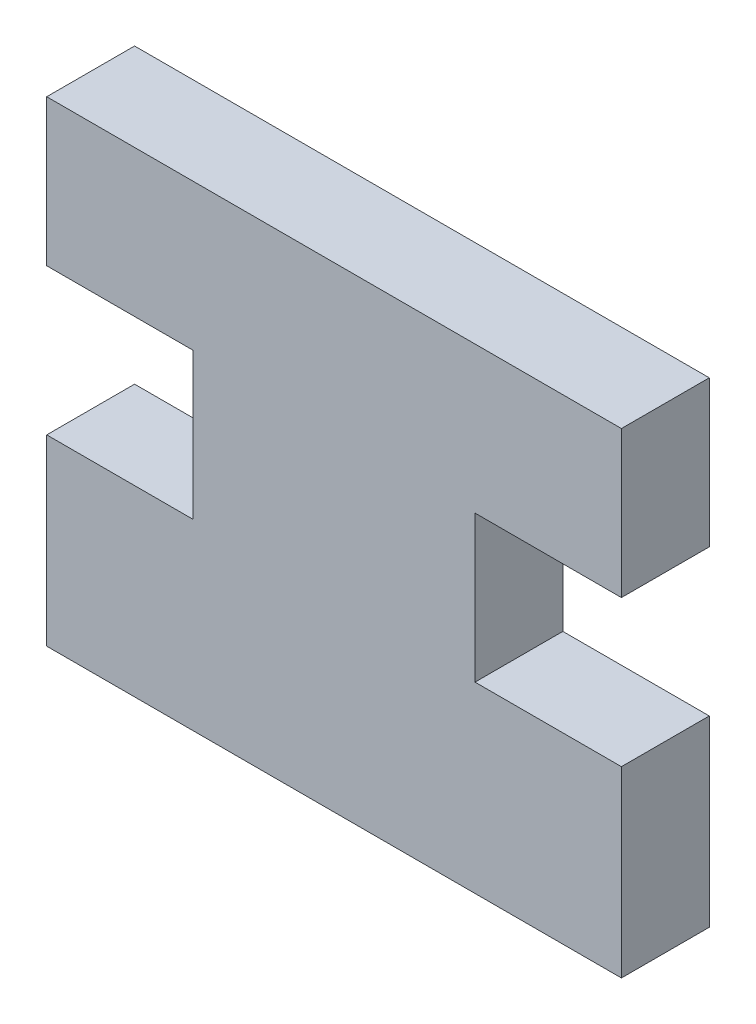
SolidWorks part; units mm, degrees
material "PBT General Purpose"
ref_plane "Front Plane" through (0, 0, 0) normal (0, 0, 1) x (1, 0, 0)
ref_plane "Top Plane" through (0, 0, 0) normal (0, 1, 0) x (1, 0, 0)
ref_plane "Right Plane" through (0, 0, 0) normal (1, 0, 0) x (0, 0, -1)
sketch "Sketch1" plane through (0, 0, 0) normal (0, 0, 1) x (1, 0, 0)
  line L0 (0, 0) -> (0, 0.5)
  line L1 (0, 0.5) -> (0.4, 0.5)
  line L2 (0.4, 0.5) -> (0.4, 0.9)
  line L3 (0.4, 0.9) -> (0, 0.9)
  line L4 (0, 0.9) -> (0, 1.3)
  line L5 (0, 1.3) -> (1.57, 1.3)
  line L6 (1.57, 1.3) -> (1.57, 0.9)
  line L7 (1.57, 0.9) -> (1.17, 0.9)
  line L8 (1.17, 0.9) -> (1.17, 0.5)
  line L9 (1.17, 0.5) -> (1.57, 0.5)
  line L10 (1.57, 0.5) -> (1.57, 0)
  line L11 (1.57, 0) -> (0, 0)
  dimension "D1" = 0.4
  dimension "D2" = 0.4
  dimension "D3" = 0.77
  dimension "D4" = 0.4
  dimension "D5" = 0.4
  dimension "D6" = 0.5
  dimension "D7" = 0.4
extrude "Boss-Extrude1" add sketch "Sketch1" along normal blind 0.24
